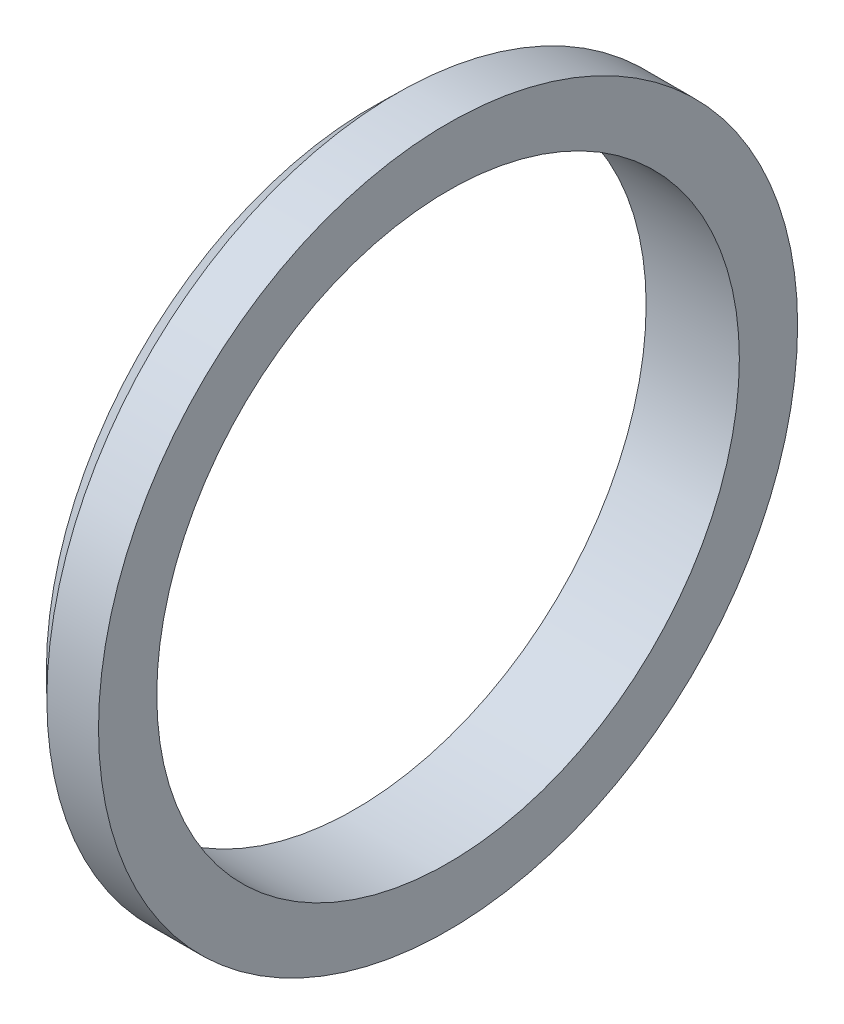
SolidWorks part; units mm, degrees
ref_plane "Front Plane" through (0, 0, 0) normal (0, 0, 1) x (1, 0, 0)
ref_plane "Top Plane" through (0, 0, 0) normal (0, 1, 0) x (1, 0, 0)
ref_plane "Right Plane" through (0, 0, 0) normal (1, 0, 0) x (0, 0, -1)
sketch "Sketch1" plane through (0, 0, 0) normal (0, 0, 1) x (1, 0, 0)
  line L0 (0, 0) -> (17.4728, 0) construction
  line L1 (-0.0743, 12.5) -> (3.9257, 12.5)
  line L2 (3.9257, 12.5) -> (3.9257, 15)
  line L3 (3.9257, 15) -> (1.7085, 15)
  line L4 (1.7085, 15) -> (0.6335, 13.9444)
  line L6 (-0.0743, 12.8161) -> (-0.0743, 12.5)
  line L7 (0.2138, 13.1322) -> (0.6335, 13.1322)
  line L8 (0.6335, 13.1322) -> (0.6335, 13.9444)
  line L9 (-0.0743, 12.8161) -> (0.2138, 13.1322)
  dimension "D1" = 25
  dimension "D2" = 30
  dimension "D3" = 4
revolve "Revolve1" add sketch "Sketch1" angle 360 about L0
